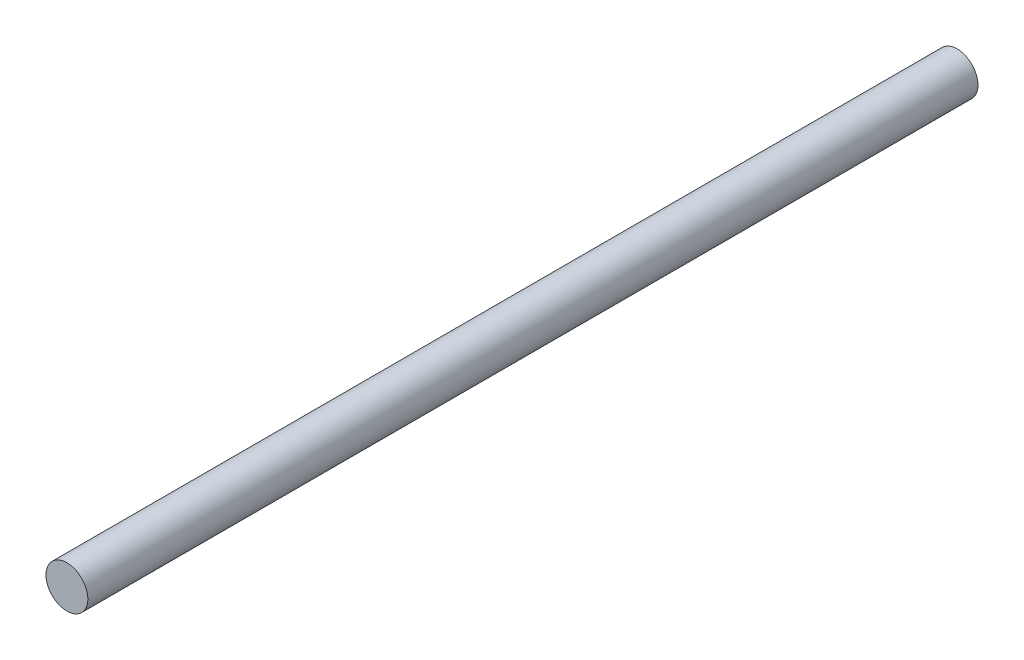
SolidWorks part; units mm, degrees
ref_plane "前视基准面" through (0, 0, 0) normal (0, 0, 1) x (1, 0, 0)
ref_plane "上视基准面" through (0, 0, 0) normal (0, 1, 0) x (1, 0, 0)
ref_plane "右视基准面" through (0, 0, 0) normal (1, 0, 0) x (0, 0, -1)
sketch "草图1" plane through (0, 0, 0) normal (0, 0, 1) x (1, 0, 0)
  circle A0 centre (0, 0) radius 6
extrude "凸台-拉伸1" add sketch "草图1" along normal blind 255
